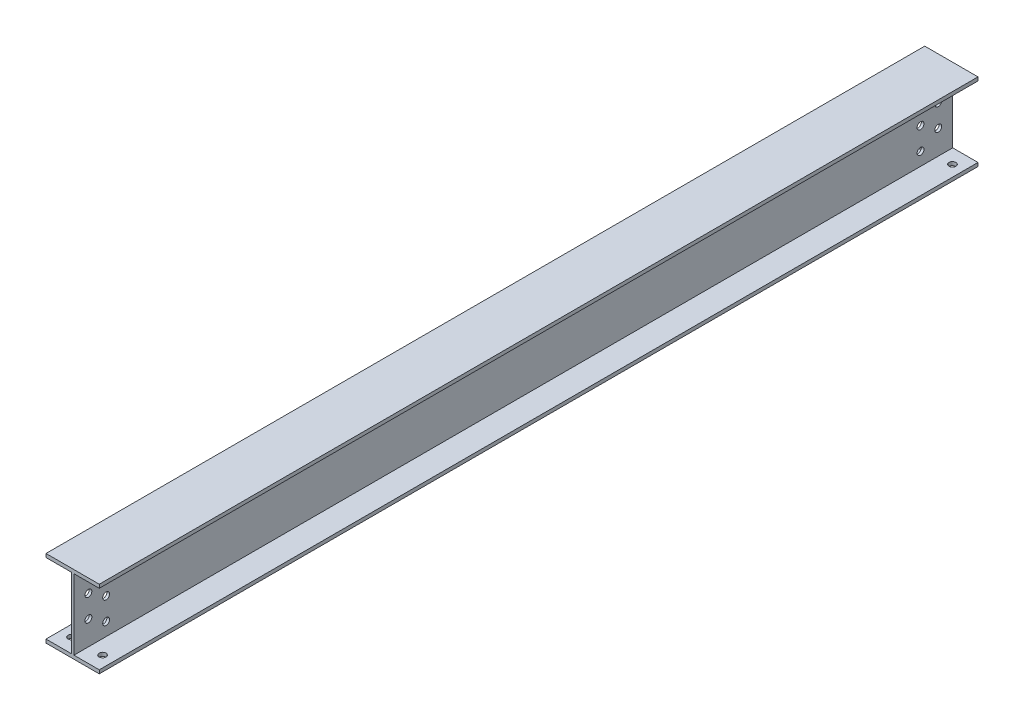
SolidWorks part; units mm, degrees
ref_plane "前视基准面" through (0, 0, 0) normal (0, 0, 1) x (1, 0, 0)
ref_plane "上视基准面" through (0, 0, 0) normal (0, 1, 0) x (1, 0, 0)
ref_plane "右视基准面" through (0, 0, 0) normal (1, 0, 0) x (0, 0, -1)
sketch "草图1" plane through (0, 0, 0) normal (0, 0, 1) x (1, 0, 0)
  line L0 (-6, 159) -> (-120, 159)
  line L1 (-120, 159) -> (-120, 175)
  line L2 (-120, 175) -> (120, 175)
  line L3 (120, 175) -> (120, 159)
  line L4 (120, 159) -> (6, 159)
  line L5 (6, 159) -> (6, -159)
  line L6 (6, -159) -> (120, -159)
  line L7 (120, -159) -> (120, -175)
  line L8 (120, -175) -> (-120, -175)
  line L9 (-120, -175) -> (-120, -159)
  line L10 (-120, -159) -> (-6, -159)
  line L11 (-6, -159) -> (-6, 159)
  line L12 (65.7545, 0) -> (-48.2455, 0) construction
  line L15 (0, 0) -> (0, 71.1058) construction
  dimension "D1" = 350
  dimension "D2" = 240
  dimension "D3" = 12
  dimension "D4" = 16
extrude "拉伸1" add sketch "草图1" along normal mid plane 3960
sketch "草图2" plane through (0, 0, 0) normal (1, 0, 0) x (0, 0, -1)
  line L0 (-1980, -159) -> (-1980, 159) construction
  line L3 (0, 386.6401) -> (0, -341.8233) construction
  line L5 (-1980, 175) -> (1980, 175) construction
  circle A0 centre (-1915, 50) radius 15.5
  circle A1 centre (-1835, 0) radius 15.5
  circle A2 centre (-1835, 100) radius 15.5
  circle A3 centre (-1835, -100) radius 15.5
  circle A4 centre (-1915, -50) radius 15.5
  circle A5 centre (1915, -50) radius 15.5
  circle A6 centre (1835, -100) radius 15.5
  circle A7 centre (1835, 100) radius 15.5
  circle A8 centre (1835, 0) radius 15.5
  circle A9 centre (1915, 50) radius 15.5
  dimension "D1" = 31
  dimension "D4" = 50
  dimension "D5" = 50
  dimension "D2" = 65
  dimension "D3" = 100
  dimension "D6" = 80
  dimension "D7" = 50
  dimension "D8" = 75
extrude "拉伸2" cut sketch "草图2" against normal through all and the other way through all
sketch "草图5" plane through (0, -159, 0) normal (0, 1, 0) x (1, 0, 0)
  line L0 (0, 0) -> (0, 2071.2487) construction
  line L1 (-6, 1980) -> (-120, 1980) construction
  line L2 (0, 0) -> (-563.3076, 0) construction
  circle A0 centre (-70, 1915) radius 15.5
  circle A1 centre (70, 1915) radius 15.5
  circle A2 centre (70, -1915) radius 15.5
  circle A3 centre (-70, -1915) radius 15.5
  dimension "D1" = 31
  dimension "D2" = 31
  dimension "D3" = 70
  dimension "D4" = 70
  dimension "D5" = 65
extrude "拉伸4" cut sketch "草图5" against normal through all
